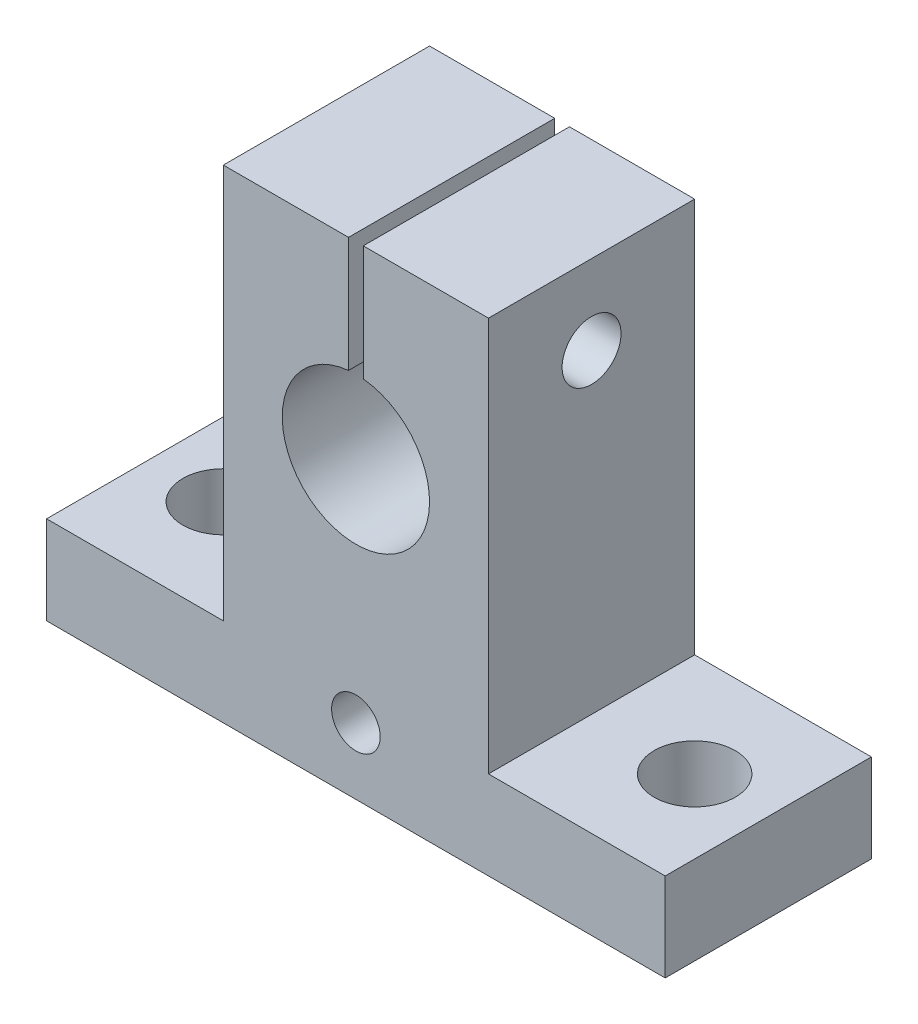
SolidWorks part; units mm, degrees
material "6061 合金"
ref_plane "前视基准面" through (0, 0, 0) normal (0, 0, 1) x (1, 0, 0)
ref_plane "上视基准面" through (0, 0, 0) normal (0, 1, 0) x (1, 0, 0)
ref_plane "右视基准面" through (0, 0, 0) normal (1, 0, 0) x (0, 0, -1)
sketch "草图3" plane through (0, 0, 0) normal (0, 0, 1) x (1, 0, 0)
  line L0 (-9, -13.4) -> (-21, -13.4)
  line L1 (-9, 13.4) -> (9, 13.4)
  line L2 (-9, 13.4) -> (-9, -13.4)
  line L3 (21, -13.4) -> (21, -19.4)
  line L4 (9, 13.4) -> (9, -13.4)
  line L5 (-9, 13.4) -> (9, -13.4) construction
  line L6 (-9, -13.4) -> (9, 13.4) construction
  line L7 (-21, -13.4) -> (-21, -19.4)
  line L8 (-21, -19.4) -> (21, -19.4)
  line L9 (0, 12.3832) -> (0, -26.3345) construction
  line L10 (9, -13.4) -> (21, -13.4)
  circle A0 centre (0, 0.6) radius 5
  point P0 (0, 0)
  point P14 (0, -19.4)
  dimension "D1" = 20
  dimension "D6" = 10
  dimension "D2" = 26.8
  dimension "D3" = 18
  dimension "D4" = 6
  dimension "D5" = 21
extrude "凸台-拉伸3" add sketch "草图3" along normal mid plane 14
sketch "草图5" plane through (0, -13.4, 0) normal (0, 1, 0) x (1, 0, 0)
  line L0 (0, 7.7672) -> (0, -15.7864) construction
  circle A0 centre (-16, 0) radius 2.75
  circle A1 centre (16, 0) radius 2.75
  dimension "D1" = 5.5
  dimension "D2" = 32
extrude "切除-拉伸1" cut sketch "草图5" against normal blind 10
sketch "草图6" plane through (0, 0, 7) normal (0, 0, 1) x (1, 0, 0)
  line L1 (-0.5, 16.5999) -> (0.5, 16.5999)
  line L2 (-0.5, 16.5999) -> (-0.5, 3.4601)
  line L3 (-0.5, 3.4601) -> (0.5, 3.4601)
  line L4 (0.5, 16.5999) -> (0.5, 3.4601)
  line L5 (-0.5, 16.5999) -> (0.5, 3.4601) construction
  line L6 (-0.5, 3.4601) -> (0.5, 16.5999) construction
  point P0 (0, 10.03)
  dimension "D1" = 1
extrude "切除-拉伸2" cut sketch "草图6" against normal up to surface (14 mm away) up to face at (0, -8.2, -7)
sketch "草图7" plane through (9, 0, 0) normal (1, 0, 0) x (0, 0, -1)
  circle A0 centre (0, 8) radius 2
  dimension "D1" = 4
  dimension "D2" = 8
extrude "切除-拉伸3" cut sketch "草图7" against normal through all
sketch "草图8" plane through (0, 0, 7) normal (0, 0, 1) x (1, 0, 0)
  line L0 (0, -14.9) -> (0, 0) construction
  circle A0 centre (0, -14.9) radius 2
  arc A1 (-0.5, 5.5749) -> (0.5, 5.5749) centre (0, 0.6) ccw construction
  dimension "D1" = 4
  dimension "D2" = 15.5
hole_wizard "M4 螺纹孔1" positions "草图10" profile "草图9" tap size "M4" standard "GB" end condition through all
sketch "草图10" plane through (0, 0, 7) normal (0, 0, 1) x (1, 0, 0)
  point P0 (0, -14.9)
cosmetic thread "孔螺蚊线1" parameters "D2"=4
sketch "草图9" plane through (0, -14.9, 7) normal (1, 0, 0) x (0, -1, 0)
  line L0 (0, 0) -> (0, 14)
  line L1 (0, 14) -> (1.65, 14)
  line L2 (1.65, 14) -> (1.65, 0)
  line L5 (1.65, 0) -> (0, 0)
  line L11 (0, -6.35) -> (0, 107.95) construction
  dimension "通孔螺纹孔钻头直径" = 3.3
  dimension "通孔螺纹孔钻头深度" = 14
